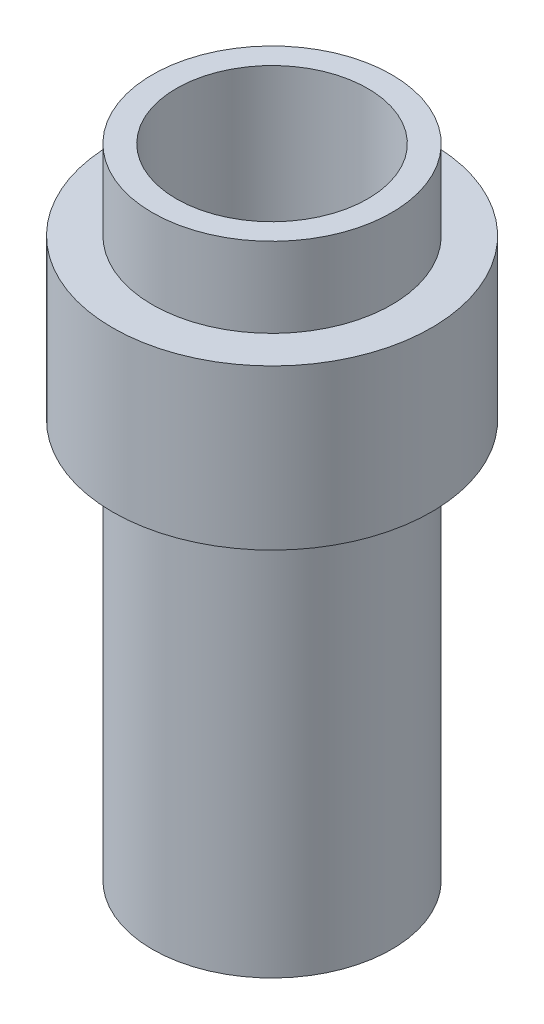
SolidWorks part; units mm, degrees
ref_plane "Front Plane" through (0, 0, 0) normal (0, 0, 1) x (1, 0, 0)
ref_plane "Top Plane" through (0, 0, 0) normal (0, 1, 0) x (1, 0, 0)
ref_plane "Right Plane" through (0, 0, 0) normal (1, 0, 0) x (0, 0, -1)
sketch "Sketch1" plane through (0, 0, 0) normal (0, 1, 0) x (1, 0, 0)
  circle A0 centre (0, 0) radius 7.5
  circle A1 centre (0, 0) radius 6
  dimension "D1" = 15
  dimension "D2" = 12
extrude "Boss-Extrude1" add sketch "Sketch1" along normal blind 40
sketch "Sketch2" plane through (0, 40, 0) normal (0, 1, 0) x (1, 0, 0)
  circle A0 centre (0, 0) radius 7.5
  circle A1 centre (0, 0) radius 10
  dimension "D1" = 15
  dimension "D2" = 20
extrude "Boss-Extrude2" add sketch "Sketch2" against normal blind 10 from offset 5
